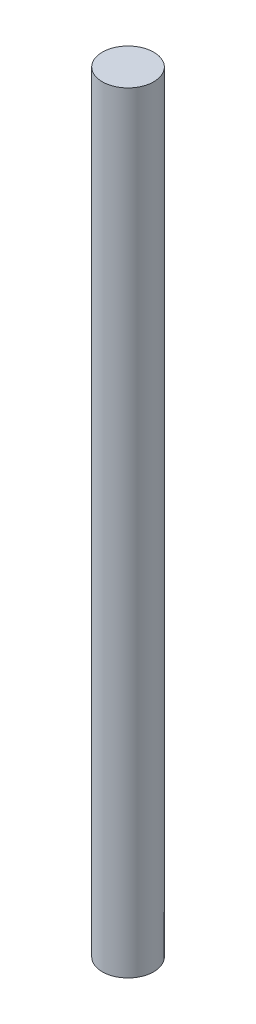
SolidWorks part; units mm, degrees
material "1060 Alloy"
ref_plane "Front Plane" through (0, 0, 0) normal (0, 0, 1) x (1, 0, 0)
ref_plane "Top Plane" through (0, 0, 0) normal (0, 1, 0) x (1, 0, 0)
ref_plane "Right Plane" through (0, 0, 0) normal (1, 0, 0) x (0, 0, -1)
sketch "Sketch2" plane through (0, 0, 0) normal (0, 1, 0) x (1, 0, 0)
  circle A0 centre (0, 0) radius 1.5
  dimension "D1" = 3
extrude "Boss-Extrude1" add sketch "Sketch2" along normal mid plane 45 contours A0
